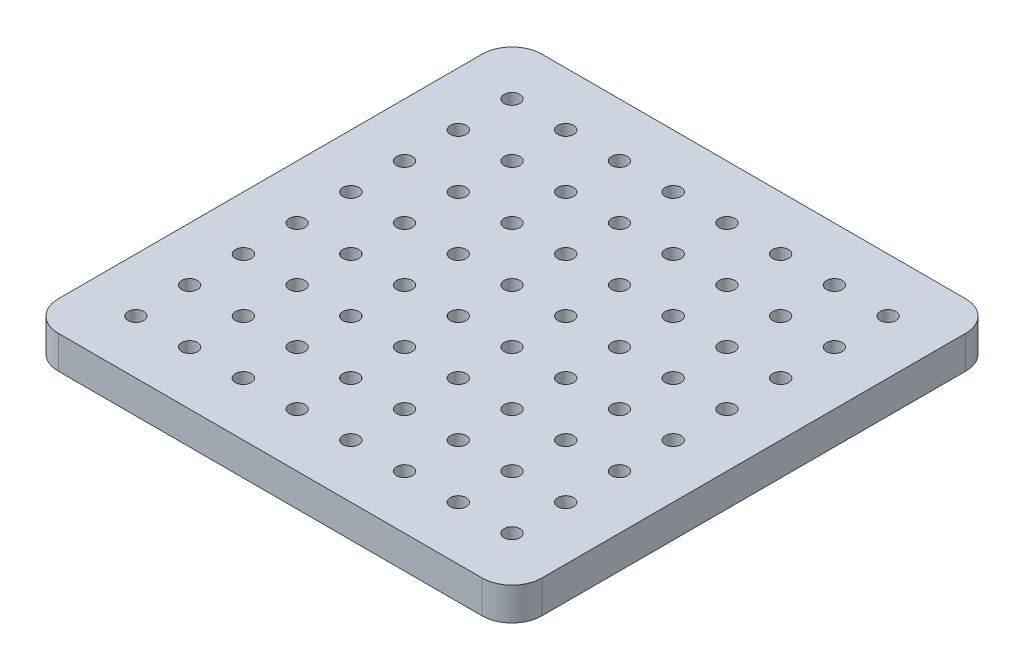
SolidWorks part; units mm, degrees
ref_plane "Front Plane" through (0, 0, 0) normal (0, 0, 1) x (1, 0, 0)
ref_plane "Top Plane" through (0, 0, 0) normal (0, 1, 0) x (1, 0, 0)
ref_plane "Right Plane" through (0, 0, 0) normal (1, 0, 0) x (0, 0, -1)
sketch "Sketch1" plane through (0, 0, 0) normal (0, 1, 0) x (1, 0, 0)
  line L1 (-81, 81) -> (81, 81)
  line L2 (-81, 81) -> (-81, -81)
  line L3 (-81, -81) -> (81, -81)
  line L4 (81, 81) -> (81, -81)
  line L5 (-81, 81) -> (81, -81) construction
  line L6 (-81, -81) -> (81, 81) construction
  point P0 (0, 0)
  dimension "D1" = 162
extrude "Boss-Extrude1" add sketch "Sketch1" along normal mid plane 11
sketch "Sketch2" plane through (0, 5.5, 0) normal (0, 1, 0) x (1, 0, 0)
  line L0 (0, 0) -> (0, -9) construction
  line L1 (0, -9) -> (9, -9) construction
  line L2 (9, -9) -> (27, -9) construction
  line L3 (27, -9) -> (45, -9) construction
  line L4 (45, -9) -> (63, -9) construction
  circle A0 centre (9, -9) radius 2.65
  circle A1 centre (27, -9) radius 2.65
  circle A2 centre (45, -9) radius 2.65
  circle A3 centre (63, -9) radius 2.65
  circle A4 centre (9, -27) radius 2.65
  circle A5 centre (27, -27) radius 2.65
  circle A6 centre (45, -27) radius 2.65
  circle A7 centre (63, -27) radius 2.65
  circle A8 centre (9, -45) radius 2.65
  circle A9 centre (27, -45) radius 2.65
  circle A10 centre (45, -45) radius 2.65
  circle A11 centre (63, -45) radius 2.65
  circle A12 centre (9, -63) radius 2.65
  circle A13 centre (27, -63) radius 2.65
  circle A14 centre (45, -63) radius 2.65
  circle A15 centre (63, -63) radius 2.65
  dimension "D3" = 5.3
  dimension "D1" = 9
  dimension "D2" = 9
  dimension "D4" = 18
  dimension "D5" = 4
extrude "Cut-Extrude1" cut sketch "Sketch2" against normal blind 10
mirror "Mirror1" about plane through (0, 0, 0) normal (0, 0, 1) of "Cut-Extrude1"
mirror "Mirror2" about plane through (0, 0, 0) normal (1, 0, 0) of "Mirror1", "Cut-Extrude1"
fillet "Fillet1" radius 10 4 edges at (81, 0, -81) (-81, 0, -81) (81, 0, 81) (-81, 0, 81)
